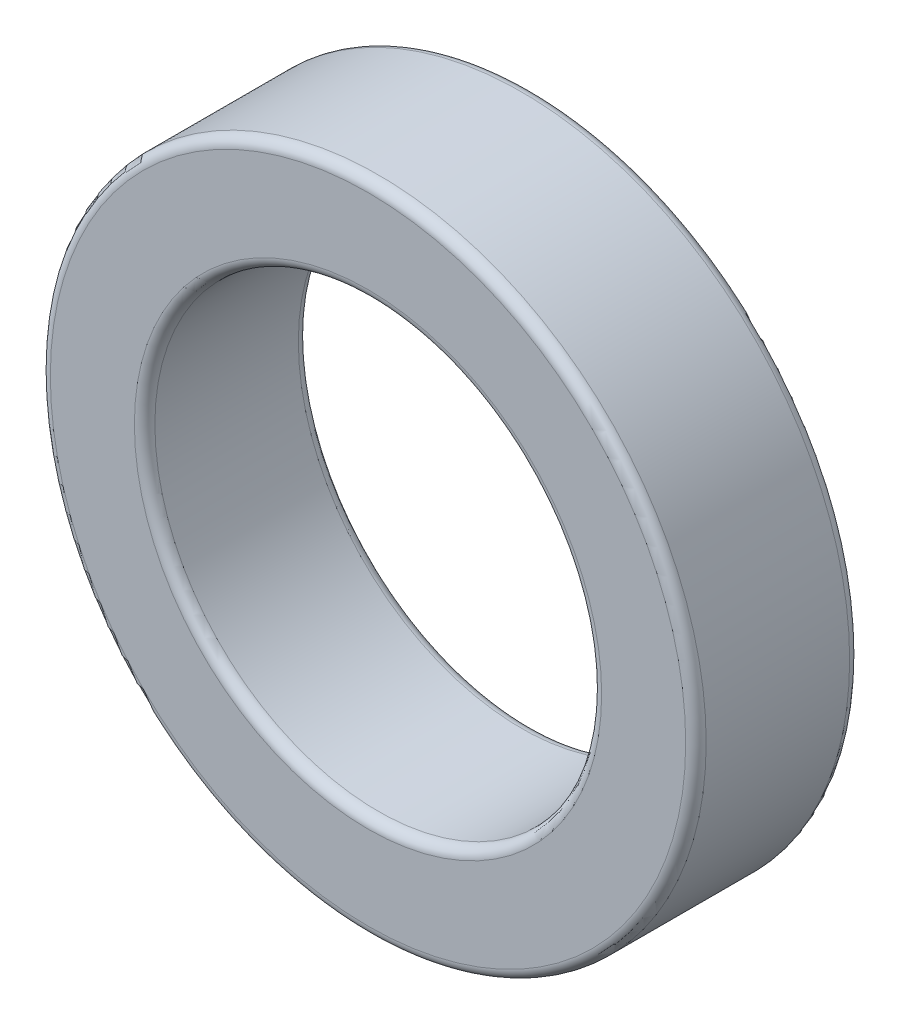
SolidWorks part; units mm, degrees
ref_plane "Front Plane" through (0, 0, 0) normal (0, 0, 1) x (1, 0, 0)
ref_plane "Top Plane" through (0, 0, 0) normal (0, 1, 0) x (1, 0, 0)
ref_plane "Right Plane" through (0, 0, 0) normal (1, 0, 0) x (0, 0, -1)
sketch "Sketch1" plane through (0, 0, 0) normal (0, 0, 1) x (1, 0, 0)
  circle A0 centre (0, 0) radius 10.9
  circle A1 centre (0, 0) radius 16
  dimension "D1" = 21.8
  dimension "D2" = 32
extrude "Boss-Extrude1" add sketch "Sketch1" along normal blind 8
fillet "Fillet1" radius 0.5 4 edges at (10.9, 0, 0) (10.9, 0, 8) (16, 0, 0) (16, 0, 8)
